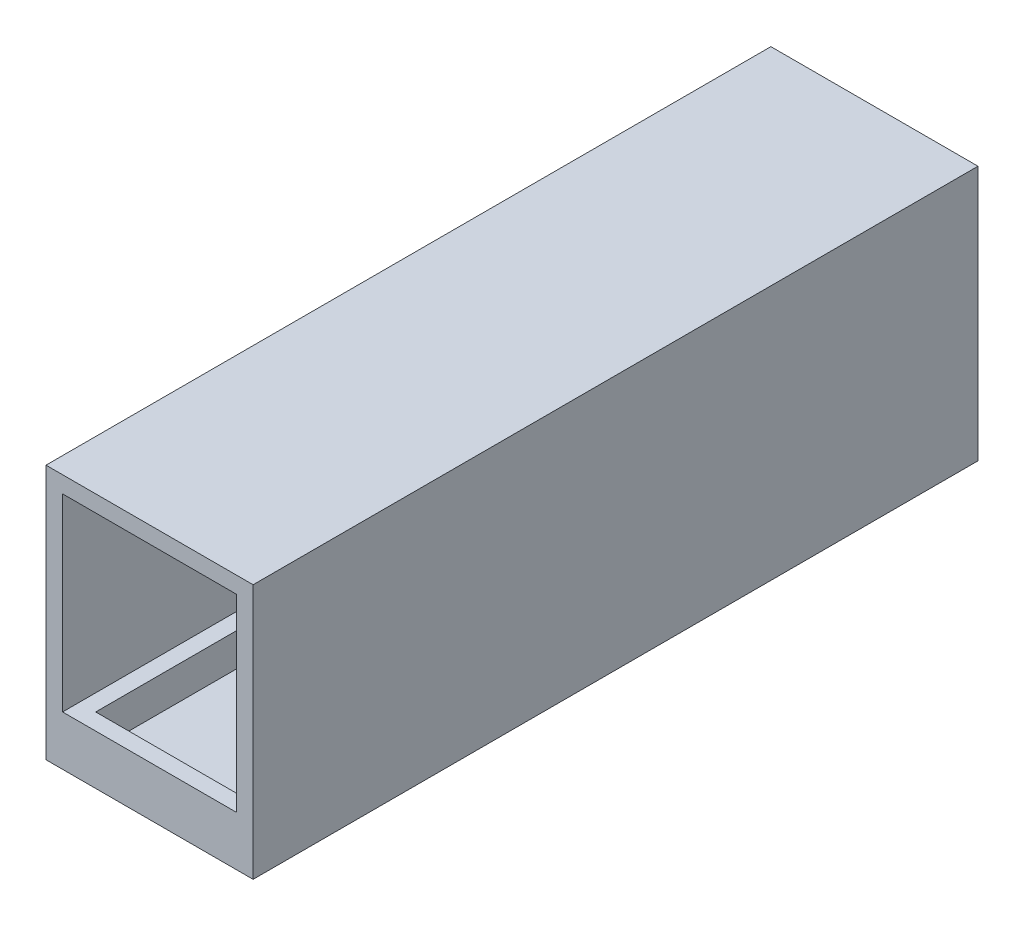
SolidWorks part; units mm, degrees
ref_plane "Front Plane" through (0, 0, 0) normal (0, 0, 1) x (1, 0, 0)
ref_plane "Top Plane" through (0, 0, 0) normal (0, 1, 0) x (1, 0, 0)
ref_plane "Right Plane" through (0, 0, 0) normal (1, 0, 0) x (0, 0, -1)
sketch "Sketch1" plane through (0, 0, 0) normal (0, 1, 0) x (1, 0, 0)
  line L0 (-33.3375, -88.9) -> (-33.3375, 88.9)
  line L1 (-26.9875, -82.55) -> (26.9875, -82.55)
  line L2 (-26.9875, -82.55) -> (-26.9875, 82.55)
  line L3 (-26.9875, 82.55) -> (26.9875, 82.55)
  line L4 (26.9875, -82.55) -> (26.9875, 82.55)
  line L5 (-26.9875, -82.55) -> (26.9875, 82.55) construction
  line L6 (-26.9875, 82.55) -> (26.9875, -82.55) construction
  line L7 (-26.9875, 88.9) -> (26.9875, 88.9)
  line L8 (33.3375, -88.9) -> (33.3375, 88.9)
  line L9 (-33.3375, -88.9) -> (33.3375, -88.9)
  line L10 (-33.3375, 88.9) -> (-33.3375, 188.9125)
  line L11 (-26.9875, 88.9) -> (26.9875, 88.9)
  line L12 (-26.9875, 88.9) -> (-26.9875, 182.5625)
  line L13 (-26.9875, 182.5625) -> (26.9875, 182.5625)
  line L14 (26.9875, 88.9) -> (26.9875, 182.5625)
  line L15 (-33.3375, 188.9125) -> (33.3375, 188.9125)
  line L16 (33.3375, 88.9) -> (33.3375, 188.9125)
  line L18 (-33.3375, 88.9) -> (33.3375, 88.9) construction
  point P0 (0, 0)
  dimension "D1" = 53.975
  dimension "D2" = 165.1
  dimension "D4" = 93.6625
  dimension "D3" = 6.35
  dimension "D5" = 6.35
extrude "Boss-Extrude4" add sketch "Sketch1" along normal blind 12.7 contours L8 L16 L15 L10 L0 L9 L4 L1 L2 L3 L14 L7 L12 L13
sketch "Sketch4" plane through (0, 0, 88.9) normal (0, 0, 1) x (1, 0, 0)
  line L0 (33.3375, 12.7) -> (33.3375, 0) construction
  line L1 (-33.3375, 0) -> (33.3375, 0)
  line L2 (-33.3375, 0) -> (-33.3375, -6.35)
  line L3 (-33.3375, -6.35) -> (33.3375, -6.35)
  line L4 (33.3375, 0) -> (33.3375, -6.35)
  dimension "D1" = 6.35
extrude "Boss-Extrude5" add sketch "Sketch4" against normal up to surface (277.8125 mm away) up to face at (0, 6.35, -188.9125)
sketch "Sketch5" plane through (0, 0, 88.9) normal (0, 0, 1) x (1, 0, 0)
  line L0 (0, 0) -> (0, -23.9633) construction
  line L3 (-39.6875, -6.35) -> (-39.6875, 91.44)
  line L4 (-39.6875, 91.44) -> (39.6875, 91.44)
  line L5 (39.6875, -6.35) -> (39.6875, 91.44)
  line L6 (-33.3375, 12.7) -> (-33.3375, -6.35) construction
  line L7 (-39.6875, -6.35) -> (-33.3375, -6.35)
  line L8 (-33.3375, -6.35) -> (-33.3375, 85.09)
  line L9 (-33.3375, 85.09) -> (33.3375, 85.09)
  line L10 (33.3375, 85.09) -> (33.3375, -6.35)
  line L12 (33.3375, -6.35) -> (39.6875, -6.35)
  line L13 (-33.3375, 12.7) -> (33.3375, 12.7) construction
  point P17 (-39.6875, 46.7377)
  point P20 (-33.3375, 12.7)
  point P21 (0, 0)
  dimension "D1" = 6.35
  dimension "D2" = 6.35
  dimension "D3" = 72.39
  dimension "D4" = 79.375
  dimension "D5" = 6.35
  dimension "D6" = 97.79
extrude "Boss-Extrude6" add sketch "Sketch5" against normal up to surface (277.8125 mm away) up to face at (0, 3.175, -188.9125)
sketch "Sketch6" plane through (0, -6.35, 0) normal (0, -1, 0) x (1, 0, 0)
  line L0 (0, 0) -> (0, 110.9177) construction
  line L2 (-39.6875, -188.9125) -> (-39.6875, 88.9) construction
  line L3 (-39.6875, -188.9125) -> (39.6875, -188.9125) construction
  circle A0 centre (-33.3375, -182.5625) radius 3.175
  circle A1 centre (33.3375, -182.5625) radius 3.175
  dimension "D1" = 6.35
  dimension "D3" = 6.35
  dimension "D2" = 6.35
extrude "Cut-Extrude3" cut sketch "Sketch6" against normal blind 6.35
